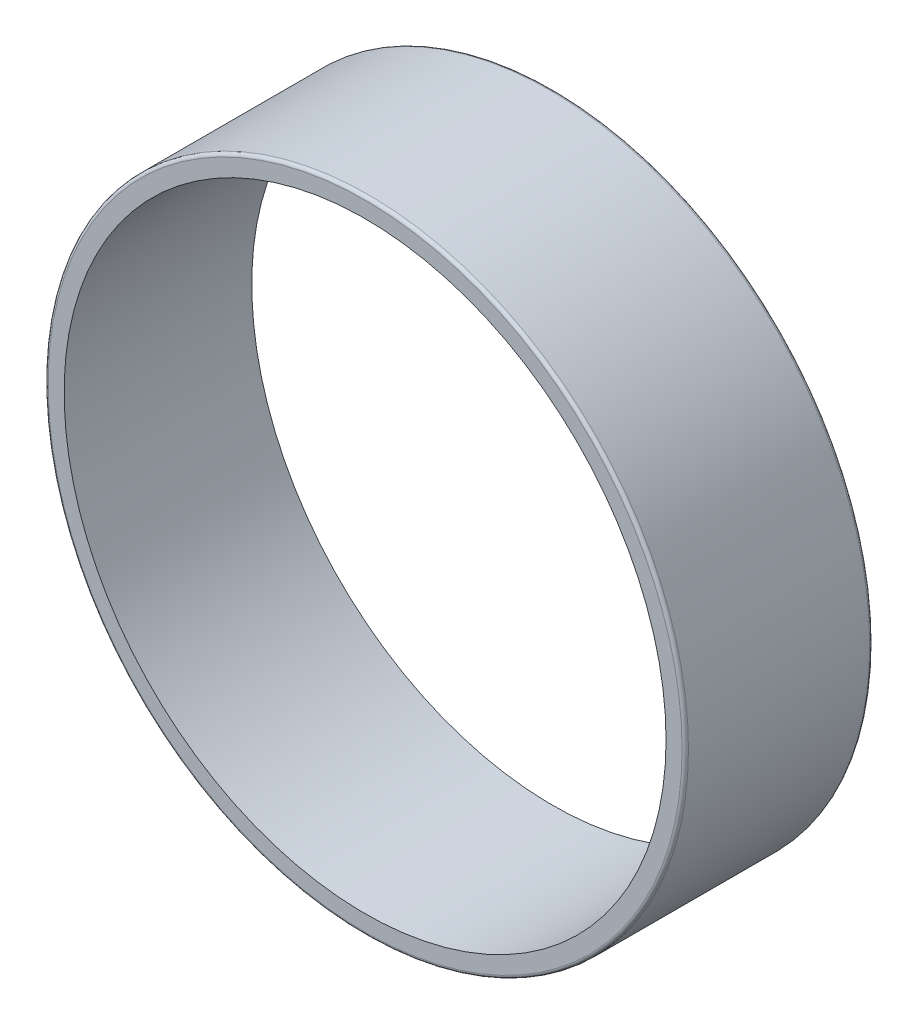
SolidWorks part; units mm, degrees
ref_plane "Front Plane" through (0, 0, 0) normal (0, 0, 1) x (1, 0, 0)
ref_plane "Top Plane" through (0, 0, 0) normal (0, 1, 0) x (1, 0, 0)
ref_plane "Right Plane" through (0, 0, 0) normal (1, 0, 0) x (0, 0, -1)
sketch "Esquisse1" plane through (0, 0, 0) normal (0, 0, 1) x (1, 0, 0)
  circle A0 centre (0, 0) radius 47
  circle A1 centre (0, 0) radius 50
  dimension "D1" = 100
  dimension "D2" = 94
extrude "Boss.-Extru.1" add sketch "Esquisse1" along normal blind 29.3
fillet "Congé1" radius 0.5 2 edges at (50, 0, 0) (50, 0, 29.3)
